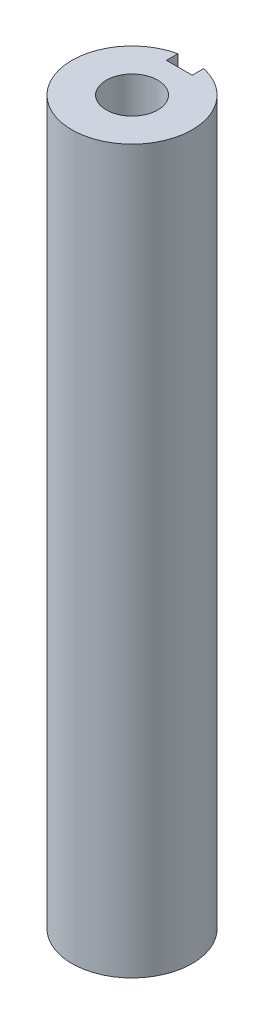
SolidWorks part; units mm, degrees
material "AISI 1045 Steel, cold drawn"
ref_plane "Front Plane" through (0, 0, 0) normal (0, 0, 1) x (1, 0, 0)
ref_plane "Top Plane" through (0, 0, 0) normal (0, 1, 0) x (1, 0, 0)
ref_plane "Right Plane" through (0, 0, 0) normal (1, 0, 0) x (0, 0, -1)
sketch "Sketch1" plane through (0, 0, 0) normal (0, 1, 0) x (1, 0, 0)
  line L0 (0, 0) -> (0, 74.8181) construction
  line L2 (-2.3813, 10.8544) -> (-2.3813, 8.7312)
  line L3 (-2.3813, 8.7312) -> (2.3813, 8.7312)
  line L4 (2.3813, 10.8544) -> (2.3813, 8.7312)
  line L5 (4.0598, 11.1125) -> (-6.0262, 11.1125) construction
  arc A1 (2.3813, 10.8544) -> (-2.3813, 10.8544) centre (0, 0) cw
  circle A2 centre (0, 0) radius 4.7625
  dimension "D1" = 6.35
  dimension "7/16" = 11.1125
  dimension "D2" = 4.7625
  dimension "D3" = 2.3813
extrude "Shaft" add sketch "Sketch1" along normal blind 133.35
sketch "Sketch3" plane through (0, 0, 0) normal (0, 0, 1) x (1, 0, 0)
  line L0 (0, 0) -> (0, 129.54)
  circle A0 centre (0, 129.54) radius 1.7859
  circle A1 centre (0, 129.54) radius 1.7859 construction
extrude "Cut-Extrude1" [suppressed] cut sketch "Sketch3" against normal through all both and the other way through all
chamfer "Chamfer1" [suppressed] distance 0.254 angle 45
